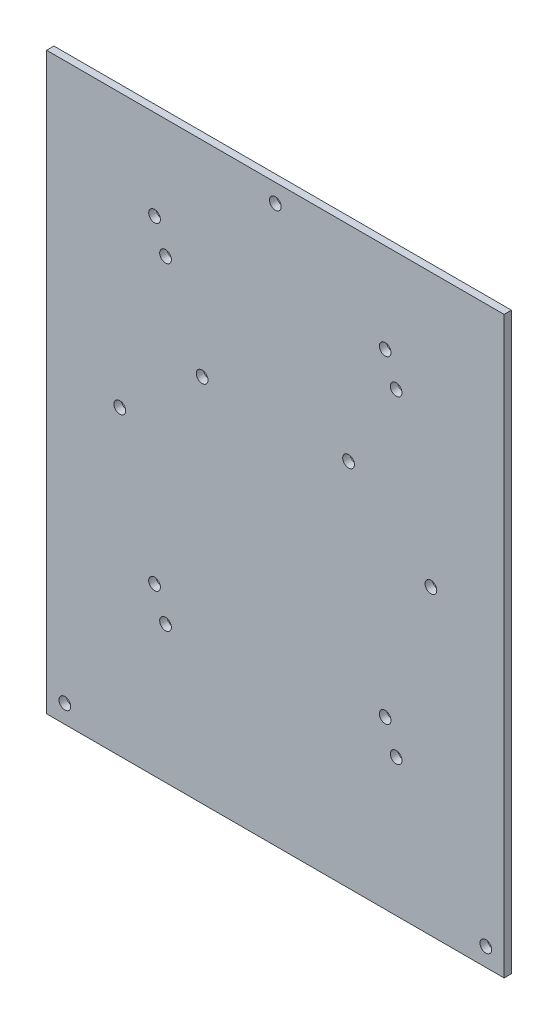
SolidWorks part; units mm, degrees
ref_plane "前基準面" through (0, 0, 0) normal (0, 0, 1) x (1, 0, 0)
ref_plane "上基準面" through (0, 0, 0) normal (0, 1, 0) x (1, 0, 0)
ref_plane "右基準面" through (0, 0, 0) normal (1, 0, 0) x (0, 0, -1)
sketch "草圖1" plane through (0, 0, 0) normal (0, 0, 1) x (1, 0, 0)
  line L0 (-62.5, 0) -> (62.5, 0)
  line L1 (62.5, 0) -> (62.5, 157)
  line L2 (-62.5, 0) -> (-62.5, 157)
  line L3 (-62.5, 157) -> (62.5, 157)
  line L4 (36.5, 136) -> (26.5, 136)
  line L5 (26.5, 121) -> (26.5, 136)
  line L6 (62.5, 85) -> (-62.5, 85) construction
  line L7 (0, 157) -> (0, 0) construction
  line L8 (-36.5, 34) -> (-26.5, 34)
  line L9 (36.5, 49) -> (26.5, 49)
  line L10 (36.5, 49) -> (36.5, 34)
  line L11 (36.5, 34) -> (26.5, 34)
  line L12 (26.5, 49) -> (26.5, 34)
  line L13 (-26.5, 49) -> (-26.5, 34)
  line L14 (-36.5, 49) -> (-26.5, 49)
  line L15 (-36.5, 49) -> (-36.5, 34)
  line L16 (36.5, 121) -> (26.5, 121)
  line L17 (36.5, 121) -> (36.5, 136)
  line L18 (-36.5, 121) -> (-36.5, 136)
  line L19 (-36.5, 121) -> (-26.5, 121)
  line L20 (-26.5, 121) -> (-26.5, 136)
  line L21 (-36.5, 136) -> (-26.5, 136)
  circle A1 centre (0, 152) radius 1.6
  circle A2 centre (20, 101) radius 1.6
  circle A3 centre (-20, 101) radius 1.6
  circle A4 centre (42.5, 82.5) radius 1.6
  circle A5 centre (-42.5, 82.5) radius 1.6
  circle A6 centre (57.5, 5) radius 1.6
  circle A7 centre (-57.5, 5) radius 1.6
  circle A8 centre (30, 45.5) radius 1.6
  circle A9 centre (33, 37.5) radius 1.6
  circle A10 centre (-33, 45.5) radius 1.6
  circle A11 centre (-30, 37.5) radius 1.6
  circle A12 centre (33, 124.5) radius 1.6
  circle A13 centre (30, 132.5) radius 1.6
  circle A14 centre (-33, 132.5) radius 1.6
  circle A15 centre (-30, 124.5) radius 1.6
  point P4 (0, 0)
  dimension "D1" = 125
  dimension "D6" = 3.2
  dimension "D8" = 3.2
  dimension "D9" = 56
  dimension "D10" = 3.2
  dimension "D13" = 3.2
  dimension "D18" = 3.2
  dimension "D19" = 3.2
  dimension "D24" = 3.2
  dimension "D25" = 3.2
  dimension "D31" = 3.2
  dimension "D32" = 3.2
  dimension "D37" = 3.2
  dimension "D40" = 3.2
  dimension "D2" = 157
  dimension "D3" = 40
  dimension "D4" = 85
  dimension "D5" = 115
  dimension "D7" = 5
  dimension "D11" = 74.5
  dimension "D12" = 5
  dimension "D14" = 26
  dimension "D15" = 15
  dimension "D16" = 10
  dimension "D17" = 34
  dimension "D20" = 3.5
  dimension "D21" = 3.5
  dimension "D22" = 3.5
  dimension "D23" = 3.5
  dimension "D26" = 3.5
  dimension "D27" = 3.5
  dimension "D28" = 3.5
  dimension "D29" = 3.5
  dimension "D30" = 85
  dimension "D33" = 3.5
  dimension "D34" = 3.5
  dimension "D35" = 3.5
  dimension "D36" = 3.5
  dimension "D38" = 3.5
  dimension "D39" = 3.5
  dimension "D41" = 3.5
  dimension "D42" = 3.5
extrude "填料-伸長1" add sketch "草圖1" along normal blind 2 contours L3 L2 L0 L1 A5 A4 L18 L21 L20 L19 L12 L9 L10 L11 L15 L14 L13 L8 L17 L16 L5 L4 A1 A2 A3 A6 A7 | L16 L17 L4 L5 A13 A12 | L21 L18 L19 L20 A15 A14 | L14 L15 L8 L13 A11 A10 | L9 L12 L11 L10 A9 A8
